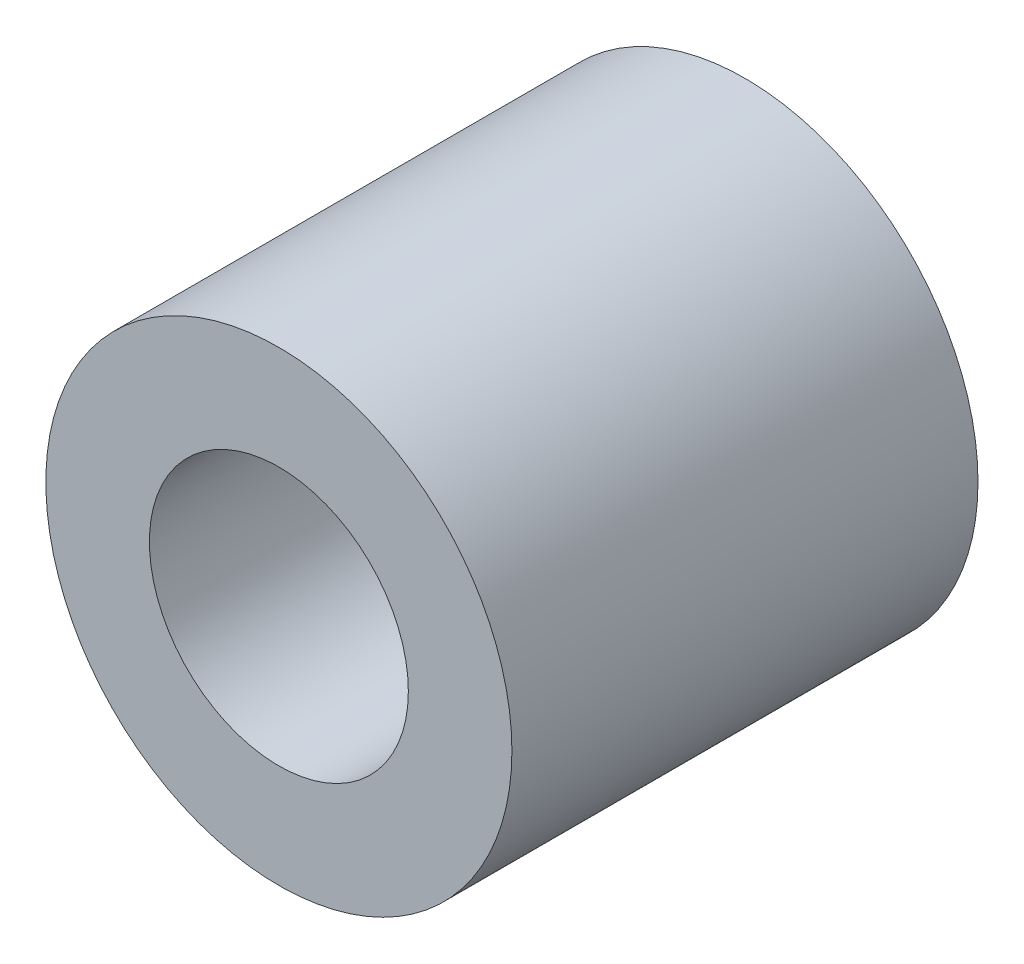
SolidWorks part; units mm, degrees
ref_plane "Plane1" through (0, 0, 0) normal (0, 0, 1) x (1, 0, 0)
ref_plane "Plane2" through (0, 0, 0) normal (0, 1, 0) x (1, 0, 0)
ref_plane "Plane3" through (0, 0, 0) normal (1, 0, 0) x (0, 0, -1)
sketch "Sketch1" plane through (0, 0, 0) normal (0, 0, 1) x (1, 0, 0)
  circle A0 centre (0, 0) radius 4.5
  dimension "D1" = 9
extrude "insert shape" add sketch "Sketch1" along normal blind 9
sketch "Sketch2" plane through (0, 0, 9) normal (0, 0, 1) x (1, 0, 0)
  line L0 (0, 0) -> (0, 5.7005) construction
  line L1 (-0.05, 4.4997) -> (0, 4.5997)
  line L2 (0.05, 4.4997) -> (0, 4.5997)
  line L3 (-0.05, 4.4997) -> (0.05, 4.4997)
  circle A0 centre (0, 0) radius 4.5 construction
  dimension "D1" = 0.1
  dimension "D2" = 0.1
extrude "grip ribs" [suppressed] add sketch "Sketch2" along normal up to surface (9 mm away)
pattern_circular "copy grip ribs" [suppressed] count 24 every 15
sketch "Sketch3" plane through (0, 0, 9) normal (0, 0, 1) x (1, 0, 0)
  circle A0 centre (0, 0) radius 2.5
  dimension "D1" = 5
extrude "center hole" cut sketch "Sketch3" against normal blind 4.3
sketch "Sketch4" plane through (0, 0, 4.7) normal (0, 0, 1) x (1, 0, 0)
  circle A0 centre (0, 0) radius 1.75
  dimension "D1" = 3.5
extrude "tapped hole" cut sketch "Sketch4" against normal up to next
cosmetic thread "Cosmetic Thread4" parameters "D1"=4.7, "D2"=5
